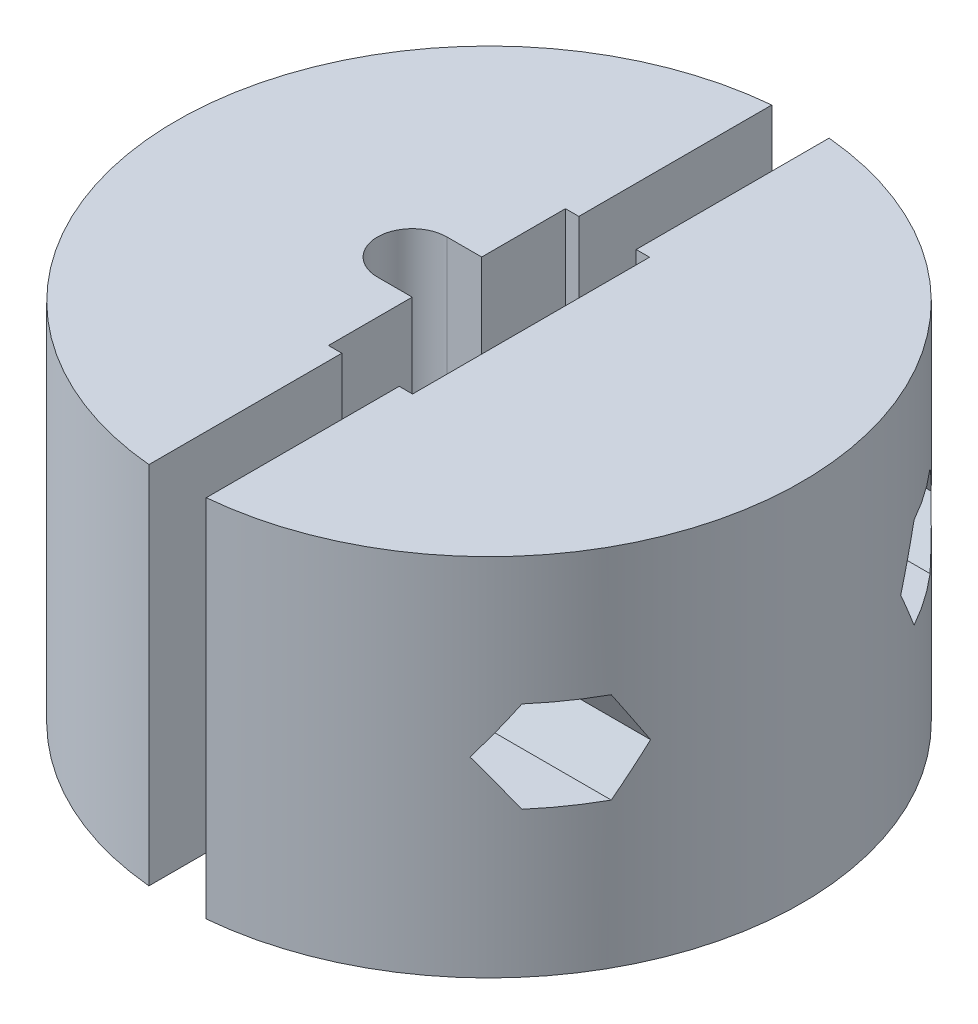
SolidWorks part; units mm, degrees
other "Markup1"
sketch "Sketch10" plane through (18, 21, 18) normal (0.9396, 0.3399, 0.0409) x (0.0435, 0, -0.9991)
ref_plane "Front Plane" through (0, 0, 0) normal (0, 0, 1) x (1, 0, 0)
ref_plane "Top Plane" through (0, 0, 0) normal (0, 1, 0) x (1, 0, 0)
ref_plane "Right Plane" through (0, 0, 0) normal (1, 0, 0) x (0, 0, -1)
sketch "Sketch1" plane through (0, 0, 0) normal (0, 1, 0) x (1, 0, 0)
  circle A0 centre (0, 0) radius 18
  dimension "D1" = 36
extrude "Boss-Extrude1" add sketch "Sketch1" along normal blind 21 contours A0
sketch "Sketch5" plane through (0, 0, 0) normal (0, -1, 0) x (-1, 0, 0)
  line L0 (-12, -2.25) -> (-12, 2.25) construction
  line L1 (-12, -2.25) -> (-12, 2.25)
  arc A0 (-12, -2.25) -> (-12, 2.25) centre (-12, 0) ccw
  dimension "D1" = 12
  dimension "D2" = 4.5
revolve "Cut-Revolve2" cut sketch "Sketch5" angle 360 about L0
ref_plane "Plane1" through (-18, 0, 0) normal (-1, 0, 0) x (0, 0, 1)
ref_plane "Plane2" through (18, 0, 0) normal (1, 0, 0) x (0, 0, -1)
sketch "Sketch6" plane through (0, 21, 0) normal (0, 1, 0) x (1, 0, 0)
  line L0 (-4.42, 2) -> (-2.42, 2)
  line L1 (-2.42, 6.82) -> (2.42, 6.82)
  line L2 (-2.42, 6.82) -> (-2.42, 2)
  line L3 (-2.42, -6.82) -> (2.42, -6.82)
  line L4 (2.42, 6.82) -> (2.42, -6.82)
  line L5 (-2.42, 6.82) -> (2.42, -6.82) construction
  line L6 (-2.42, -6.82) -> (2.42, 6.82) construction
  line L7 (-4.42, -2) -> (-2.42, -2)
  line L8 (-2.42, -2) -> (-2.42, -6.82)
  arc A0 (-4.42, 2) -> (-4.42, -2) centre (-4.42, 0) ccw
  point P0 (0, 0)
  dimension "D3" = 2
  dimension "D1" = 13.64
  dimension "D2" = 4.84
  dimension "D5" = 2
  dimension "D4" = 6.82
extrude "Cut-Extrude1" cut sketch "Sketch6" against normal through all both and the other way through all
sketch "Sketch7" plane through (-18, 0, 0) normal (-1, 0, 0) x (0, 0, 1)
  line L0 (0, 0) -> (0, 21.1129) construction
  circle A0 centre (-10.23, 11) radius 1.5
  circle A1 centre (10.23, 11) radius 1.5
  dimension "D1" = 3
  dimension "D2" = 10.23
  dimension "D3" = 11
extrude "Cut-Extrude2" cut sketch "Sketch7" against normal through all both and the other way through all
sketch "Sketch8" plane through (-18, 0, 0) normal (-1, 0, 0) x (0, 0, 1)
  circle A0 centre (-10.23, 11) radius 2.5
  circle A1 centre (10.23, 11) radius 2.5
  dimension "D1" = 5
extrude "Cut-Extrude3" cut sketch "Sketch8" against normal blind 11
sketch "Sketch9" plane through (18, 0, 0) normal (1, 0, 0) x (0, 0, -1)
  line L1 (-8.7145, 13.625) -> (-11.7455, 13.625)
  line L2 (-11.7455, 13.625) -> (-13.2611, 11)
  line L3 (-13.2611, 11) -> (-11.7455, 8.375)
  line L4 (-11.7455, 8.375) -> (-8.7145, 8.375)
  line L5 (-8.7145, 8.375) -> (-7.1989, 11)
  line L6 (-7.1989, 11) -> (-8.7145, 13.625)
  line L7 (11.7455, 13.625) -> (8.7145, 13.625)
  line L8 (8.7145, 13.625) -> (7.1989, 11)
  line L9 (7.1989, 11) -> (8.7145, 8.375)
  line L10 (8.7145, 8.375) -> (11.7455, 8.375)
  line L11 (11.7455, 8.375) -> (13.2611, 11)
  line L12 (13.2611, 11) -> (11.7455, 13.625)
  circle A0 centre (-10.23, 11) radius 2.625 construction
  circle A1 centre (10.23, 11) radius 2.625 construction
  dimension "D1" = 5.25
extrude "Cut-Extrude4" cut sketch "Sketch9" against normal blind 11
sketch "Sketch14" plane through (0, 21, 0) normal (0, 1, 0) x (1, 0, 0)
  line L0 (2.42, -6.82) -> (2.42, 6.82) construction
  line L1 (-1.65, 18) -> (1.65, 18)
  line L2 (-1.65, 18) -> (-1.65, -18)
  line L3 (-1.65, -18) -> (1.65, -18)
  line L4 (1.65, 18) -> (1.65, -18)
  line L5 (-2.42, 6.82) -> (-2.42, 2) construction
  line L6 (2.42, -6.82) -> (2.42, 6.82)
  line L7 (-2.42, 6.82) -> (-2.42, 2)
  line L8 (1.65, 0) -> (-1.65, 0) construction
  line L9 (0, 18) -> (0, -18) construction
  line M9 (2.42, -6.82) -> (-2.42, -6.82)
  line M15 (-2.42, 6.82) -> (2.42, 6.82)
  circle M16 centre (0, 0) radius 18
  dimension "D1" = 36
  dimension "D2" = 3.3
extrude "Cut-Extrude7" cut sketch "Sketch14" against normal through all contours L4 L2 M16 M15 | L4 L2 M9 M16
equation "\"stopper_dia\"= 36mm"
equation "\"shaft_dia\"= 29mm"
equation "\"D1@Sketch1\"=\"stopper_dia\""
equation "\"led_width\"= 12.4mm"
equation "\"led_height\"= 4.4mm"
equation "\"nut_depth\"= 5mm"
equation "\"D1@Sketch6\" = \"led_width\" * 1.10"
equation "\"D2@Sketch6\"= \"led_height\" * 1.10"
equation "\"length\"= 21mm"
equation "\"D3@Sketch7\"= \"length\" - 10mm"
equation "\"D1@Boss-Extrude1\"=\"length\""
equation "\"D4@Sketch6\"= \"D1@Sketch6\" / 2"
equation "\"D2@Sketch7\"=\"D1@Sketch6\"/2*1.5"
equation "\"D1@Sketch14\"=\"stopper_dia\""
equation "\"D2@Sketch14\"=\"led_height\"*0.75"
